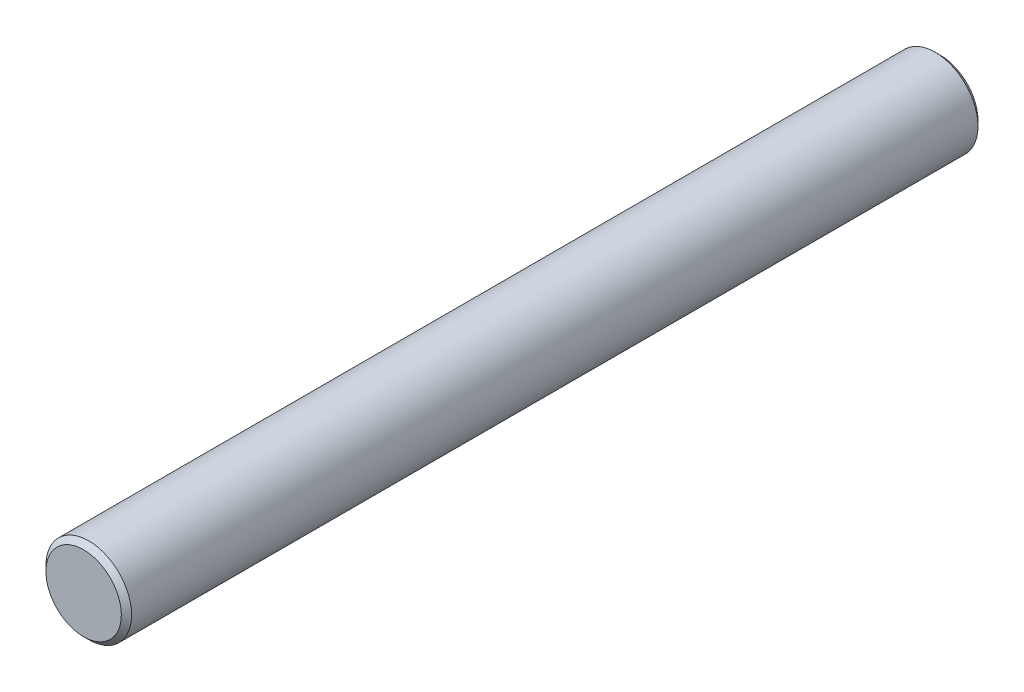
SolidWorks part; units mm, degrees
material "Простая углеродистая сталь"
ref_plane "Спереди" through (0, 0, 0) normal (0, 0, 1) x (1, 0, 0)
ref_plane "Сверху" through (0, 0, 0) normal (0, 1, 0) x (1, 0, 0)
ref_plane "Справа" through (0, 0, 0) normal (1, 0, 0) x (0, 0, -1)
sketch "Эскиз1" plane through (0, 0, 0) normal (0, 0, 1) x (1, 0, 0)
  circle A0 centre (0, 0) radius 2.5
  dimension "D1" = 5
extrude "Бобышка-Вытянуть1" add sketch "Эскиз1" along normal blind 50
chamfer "Фаска1" distance 0.3 angle 45 2 edges at (2.5, 0, 0) (2.5, 0, 50)
